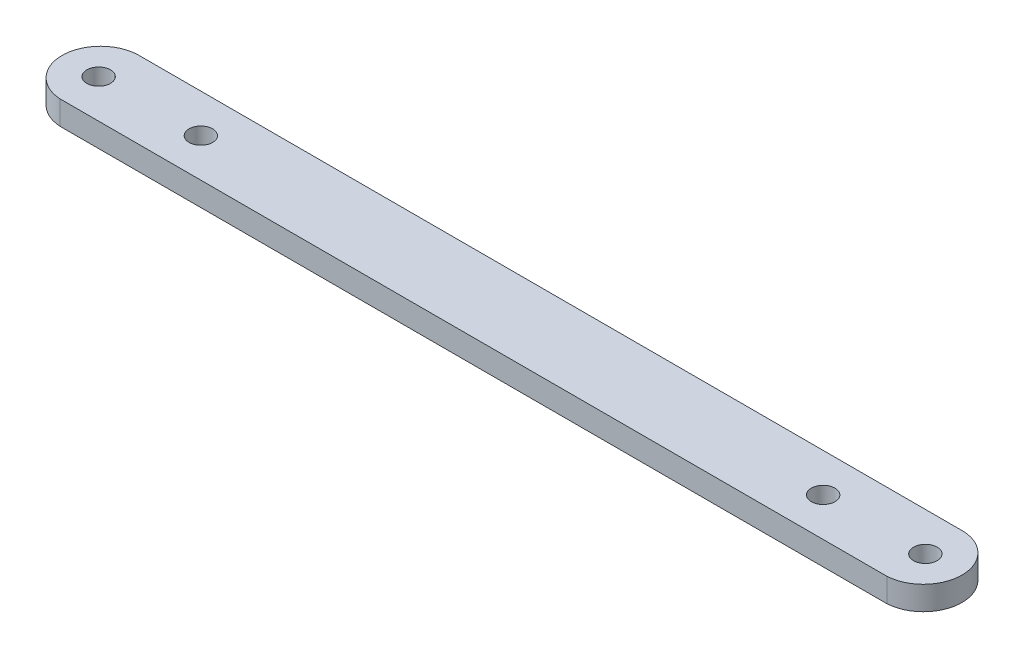
SolidWorks part; units mm, degrees
ref_plane "Front Plane" through (0, 0, 0) normal (0, 0, 1) x (1, 0, 0)
ref_plane "Top Plane" through (0, 0, 0) normal (0, 1, 0) x (1, 0, 0)
ref_plane "Right Plane" through (0, 0, 0) normal (1, 0, 0) x (0, 0, -1)
sketch "Sketch1" plane through (0, 0, 0) normal (0, 1, 0) x (1, 0, 0)
  line L0 (0, 6) -> (0, -6) construction
  line L5 (70, -6) -> (-70, 6) construction
  line L6 (70, 6) -> (-70, -6) construction
  line L7 (-64.3, 6) -> (64.3, 6)
  line L8 (-64.3, -6) -> (64.3, -6)
  circle A0 centre (-64.3, 0) radius 1.835
  circle A1 centre (-48.4, 0) radius 1.835
  circle A2 centre (64.3, 0) radius 1.835
  circle A3 centre (48.4, 0) radius 1.835
  arc A4 (-64.3, 6) -> (-64.3, -6) centre (-63.9921, 0) ccw
  arc A5 (64.3, 6) -> (64.3, -6) centre (63.9921, 0) cw
  point P0 (0, 0)
  dimension "D4" = 3.67
  dimension "D5" = 3.67
  dimension "D6" = 15.9
  dimension "D1" = 140
  dimension "D2" = 12
extrude "Boss-Extrude1" add sketch "Sketch1" along normal blind 3.7
